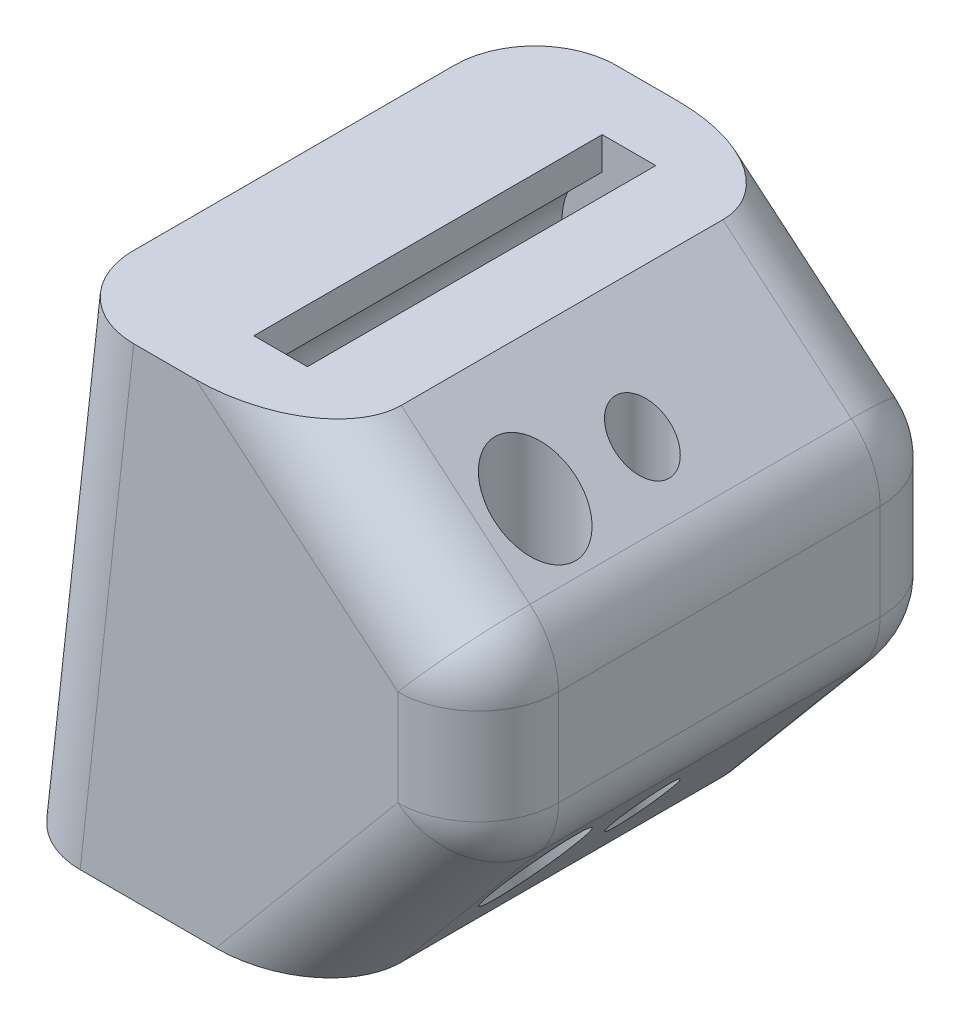
SolidWorks part; units mm, degrees
ref_plane "Front Plane" through (0, 0, 0) normal (0, 0, 1) x (1, 0, 0)
ref_plane "Top Plane" through (0, 0, 0) normal (0, 1, 0) x (1, 0, 0)
ref_plane "Right Plane" through (0, 0, 0) normal (1, 0, 0) x (0, 0, -1)
sketch "Sketch2" plane through (0, 0, 0) normal (0, 0, 1) x (1, 0, 0)
  line L0 (0, 0) -> (12, 0)
  line L1 (12, 0) -> (17.1718, 6.1635)
  line L2 (0, 0) -> (2, 18)
  line L3 (2, 18) -> (12, 18)
  line L4 (12, 18) -> (16.8021, 13.9706)
  line L5 (17.8737, 11.6725) -> (17.8737, 8.0919)
  arc A0 (16.8021, 13.9706) -> (17.8737, 11.6725) centre (14.8737, 11.6725) cw
  arc A1 (17.1718, 6.1635) -> (17.8737, 8.0919) centre (14.8737, 8.0919) ccw
  point P9 (17.8737, 13.0714)
  point P12 (17.8737, 7)
  dimension "D8" = 3
  dimension "D9" = 3
  dimension "D1" = 12
  dimension "D2" = 130
  dimension "D3" = 7
  dimension "D4" = 2
  dimension "D5" = 18
  dimension "D6" = 10
  dimension "D7" = 140
extrude "Boss-Extrude1" add sketch "Sketch2" along normal blind 18
sketch "Sketch3" plane through (0, 0, 18) normal (0, 0, 1) x (1, 0, 0)
  line L0 (12, 18) -> (2, 18) construction
  line L2 (7, 18) -> (9, 18)
  line L3 (7, 18) -> (7, 16.7913)
  line L5 (9, 18) -> (9, 16.7913)
  arc A0 (7, 16.7913) -> (9, 16.7913) centre (8, 14.5) ccw
  point P0 (8, 18)
  dimension "D2" = 5
  dimension "D1" = 8
  dimension "D3" = 3.5
  dimension "D4" = 2
  dimension "D5" = 1
extrude "Cut-Extrude1" cut sketch "Sketch3" against normal blind 13 from offset 2.5 offset against normal yes
sketch "Sketch4" plane through (0, 0, 0) normal (0, 0, -1) x (-1, 0, 0)
  line L0 (0, 0) -> (-12, 0) construction
  line L2 (-9, 0) -> (-7, 0)
  line L3 (-9, 0) -> (-9, 1.2087)
  line L5 (-7, 0) -> (-7, 1.2087)
  arc A0 (-7, 1.2087) -> (-9, 1.2087) centre (-8, 3.5) ccw
  point P0 (-8, 0)
  dimension "D2" = 5
  dimension "D1" = 8
  dimension "D3" = 3.5
  dimension "D4" = 2
  dimension "D5" = 1
extrude "Cut-Extrude2" cut sketch "Sketch4" against normal blind 13 from offset 2.5 offset against normal yes
sketch "Sketch5" plane through (0, 0, 0) normal (0, 1, 0) x (1, 0, 0)
  line L0 (12, -18) -> (12, 0) construction
  circle A0 centre (15, -9) radius 1
  circle A1 centre (15, -13) radius 1.5
  point P0 (12, -9)
  point P8 (0, 0)
  dimension "D1" = 2
  dimension "D4" = 3
  dimension "D2" = 3
  dimension "D3" = 9
  dimension "D5" = 4
extrude "Cut-Extrude3" cut sketch "Sketch5" along normal blind 25
fillet "Fillet1" radius 3 12 edges at (14.5859, 3.0818, 0) (17.6928, 7.0659, 0) (14.401, 15.9853, 0) (17.5926, 12.9403, 0) (14.5859, 3.0818, 18) (17.6928, 7.0659, 18) (14.401, 15.9853, 18) (17.5926, 12.9403, 18) (1, 9, 0) (17.8737, 9.8822, 0) (1, 9, 18) (17.8737, 9.8822, 18)
ref_plane "Plane1" through (0, 0, 9) normal (0, 0, 1) x (1, 0, 0)
